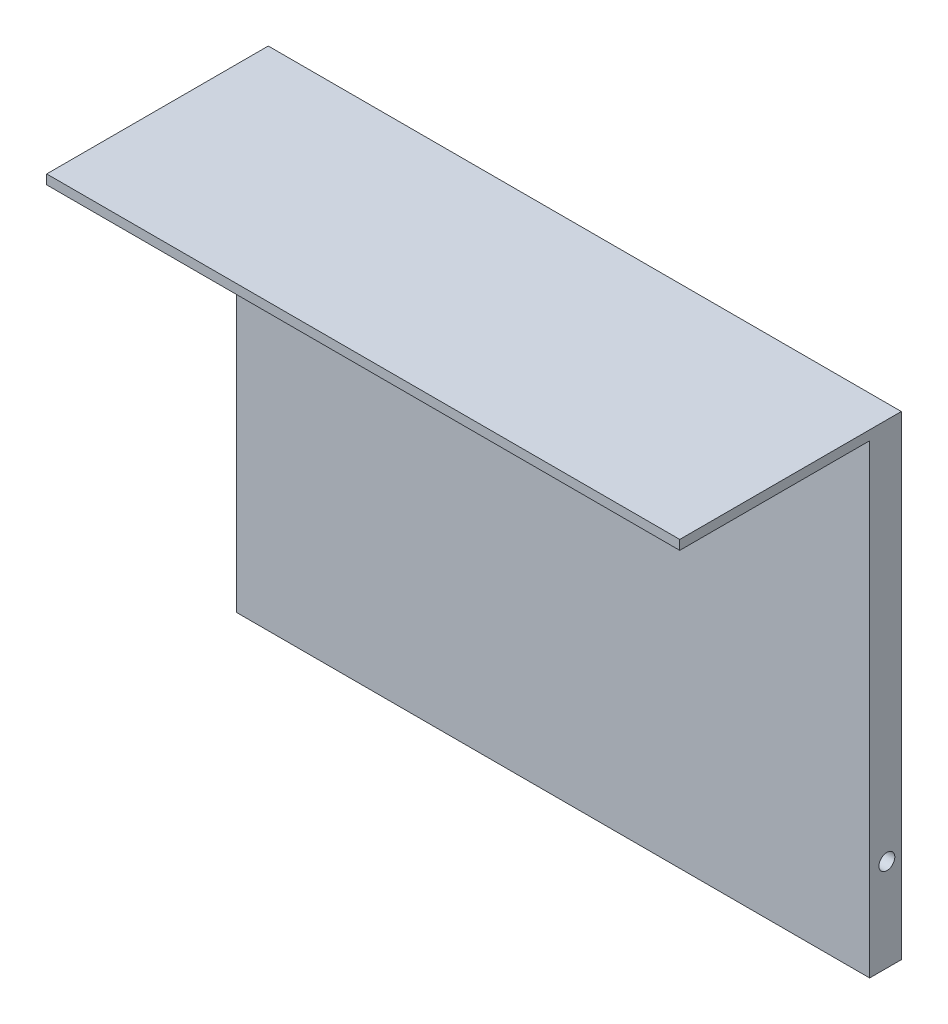
SolidWorks part; units mm, degrees
ref_plane "Front Plane" through (0, 0, 0) normal (0, 0, 1) x (1, 0, 0)
ref_plane "Top Plane" through (0, 0, 0) normal (0, 1, 0) x (1, 0, 0)
ref_plane "Right Plane" through (0, 0, 0) normal (1, 0, 0) x (0, 0, -1)
sketch "Sketch1" plane through (0, 0, 0) normal (0, 0, 1) x (1, 0, 0)
  line L1 (100, -75) -> (-100, -75)
  line L2 (100, -75) -> (100, 75)
  line L3 (100, 75) -> (-100, 75)
  line L4 (-100, -75) -> (-100, 75)
  line L5 (100, -75) -> (-100, 75) construction
  line L6 (100, 75) -> (-100, -75) construction
  point P0 (0, 0)
  dimension "D1" = 150
  dimension "D2" = 200
extrude "Boss-Extrude1" add sketch "Sketch1" along normal blind 10
sketch "Sketch2" plane through (-100, 0, 0) normal (-1, 0, 0) x (0, 0, 1)
  circle A1 centre (4.5601, -45.8566) radius 2.5
  point P0 (4.5601, -45.8566)
extrude "Cut-Extrude1" cut sketch "Sketch2" against normal through all both and the other way through all
sketch "Sketch3" plane through (0, 0, 10) normal (0, 0, 1) x (1, 0, 0)
  line L0 (100, -75) -> (100, 75) construction
  line L1 (-100, 72) -> (100, 72)
  line L2 (-100, 72) -> (-100, 75)
  line L3 (-100, 75) -> (100, 75)
  line L4 (100, 72) -> (100, 75)
  dimension "D1" = 3
extrude "Boss-Extrude2" add sketch "Sketch3" along normal blind 60
